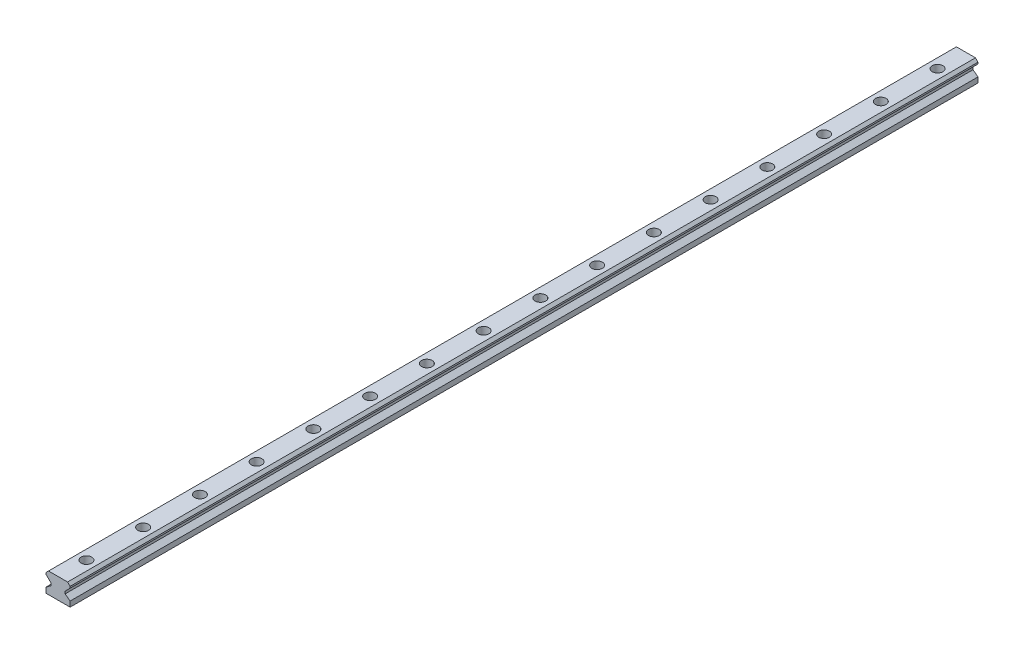
SolidWorks part; units mm, degrees
material "一般碳鋼"
ref_plane "前基準面" through (0, 0, 0) normal (0, 0, 1) x (1, 0, 0)
ref_plane "上基準面" through (0, 0, 0) normal (0, 1, 0) x (1, 0, 0)
ref_plane "右基準面" through (0, 0, 0) normal (1, 0, 0) x (0, 0, -1)
sketch "草圖1" plane through (0, 0, 0) normal (0, 0, 1) x (1, 0, 0)
  line L0 (17, 0) -> (-17, 0)
  line L1 (-17, 0) -> (-17, 7.5)
  line L2 (-17, 7.5) -> (-10, 12.7214)
  line L3 (-10, 12.7214) -> (-10, 16.1299)
  line L4 (-10, 16.1299) -> (-17, 23.1299)
  line L5 (-17, 23.1299) -> (-17, 25.4259)
  line L6 (-17, 25.4259) -> (-13.4259, 29)
  line L7 (-13.4259, 29) -> (13.4259, 29)
  line L8 (0, 29) -> (0, 0) construction
  line L9 (17, 25.4259) -> (13.4259, 29)
  line L10 (17, 23.1299) -> (17, 25.4259)
  line L11 (10, 16.1299) -> (17, 23.1299)
  line L12 (10, 12.7214) -> (10, 16.1299)
  line L13 (17, 7.5) -> (10, 12.7214)
  line L14 (17, 0) -> (17, 7.5)
  dimension "D1" = 17
  dimension "D2" = 7.5
  dimension "D3" = 29
  dimension "D4" = 135
  dimension "D5" = 135
  dimension "D6" = 10
extrude "伸長1" add sketch "草圖1" along normal mid plane 1280
hole_wizard "M8 內六角圓柱頭螺釘的柱孔1" positions "草圖3" profile "草圖2" counterbore size "M8" standard "GB" end condition through all
sketch "草圖3" plane through (0, 29, 0) normal (0, 1, 0) x (-1, 0, 0)
  line L0 (0, 640) -> (0, 701.4527) construction
  line L1 (-13.4259, 640) -> (13.4259, 640) construction
  line L6 (0, -640) -> (0, -600) construction
  line L7 (-13.4259, -640) -> (13.4259, -640) construction
  point P0 (0, -600)
  dimension "D1" = 40
sketch "草圖2" plane through (0, 29, -600) normal (1, 0, 0) x (0, 0, 1)
  line L0 (0, 0) -> (0, 29)
  line L1 (0, 29) -> (4.5, 29)
  line L3 (4.5, 29) -> (4.5, 12)
  line L4 (4.5, 12) -> (7.5, 12)
  line L5 (7.5, 12) -> (7.5, 0)
  line L7 (7.5, 0) -> (0, 0)
  line L11 (0, -6.35) -> (0, 107.95) construction
  dimension "貫穿孔直徑" = 9
  dimension "貫穿孔深度" = 29
  dimension "柱孔直徑" = 15
  dimension "柱孔深度" = 12
pattern_linear "直線複製排列1" count 16 spacing 80 along (0, 0, 1) of "M8 內六角圓柱頭螺釘的柱孔1"
